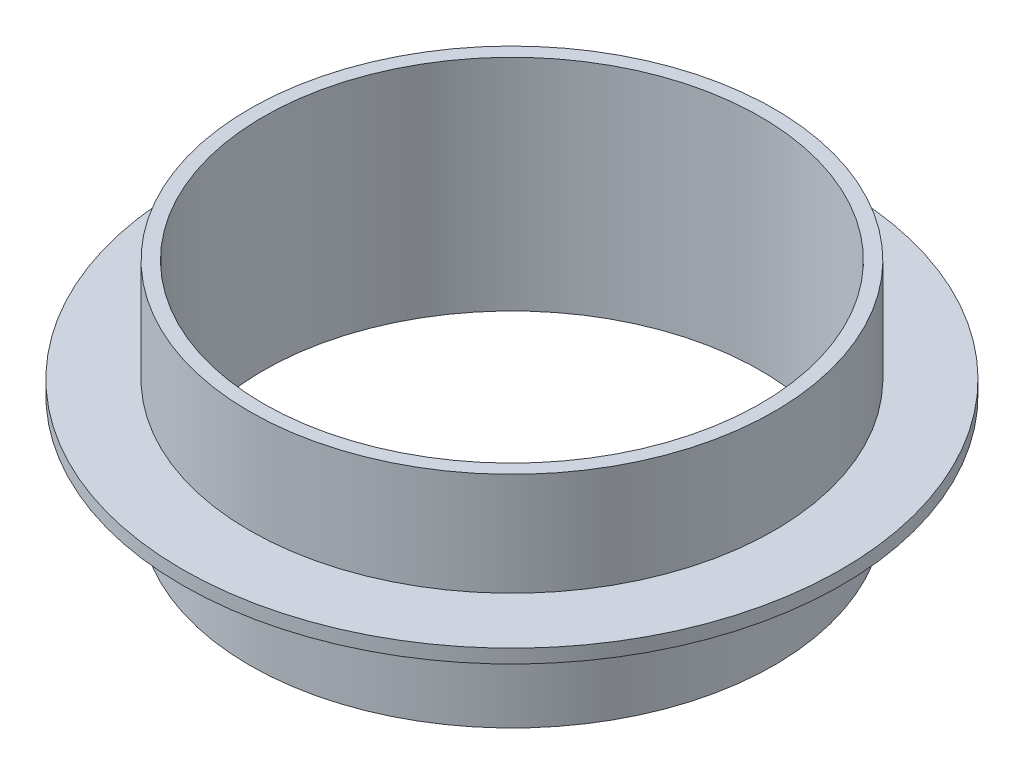
SolidWorks part; units mm, degrees
ref_plane "Front Plane" through (0, 0, 0) normal (0, 0, 1) x (1, 0, 0)
ref_plane "Top Plane" through (0, 0, 0) normal (0, 1, 0) x (1, 0, 0)
ref_plane "Right Plane" through (0, 0, 0) normal (1, 0, 0) x (0, 0, -1)
sketch "Sketch1" plane through (0, 0, 0) normal (0, 1, 0) x (1, 0, 0)
  circle A0 centre (0, 0) radius 57.4675
  circle A1 centre (0, 0) radius 60.6425
  dimension "D1" = 114.935
  dimension "D2" = 3.175
extrude "Boss-Extrude1" add sketch "Sketch1" along normal blind 50.8
sketch "Sketch2" plane through (0, 50.8, 0) normal (0, 1, 0) x (1, 0, 0)
  circle A0 centre (0, 0) radius 76.2
  circle A1 centre (0, 0) radius 60.6425 construction
  circle A2 centre (0, 0) radius 60.6425
  dimension "D1" = 152.4
extrude "Boss-Extrude2" add sketch "Sketch2" against normal blind 3.175 from offset 23.8125 offset against normal yes
hole_wizard "1/4 Clearance Hole1" positions "Sketch4" profile "Sketch3" hole size "1/4" standard "ANSI Inch"
sketch "Sketch4" plane through (0, 26.9875, 0) normal (0, 1, 0) x (1, 0, 0)
  line L0 (-76.2, 0) -> (-60.6425, 0) construction
  circle A0 centre (0, 0) radius 76.2 construction
  circle A1 centre (0, 0) radius 60.6425 construction
  point P0 (-68.4213, 0)
sketch "Sketch3" plane through (-68.4213, 26.9875, 0) normal (1, 0, 0) x (0, 0, 1)
  line L0 (0, 0) -> (0, 40.3151)
  line L1 (0, 40.3151) -> (3.2639, 38.354)
  line L2 (3.2639, 38.354) -> (3.2639, 0)
  line L5 (3.2639, 0) -> (0, 0)
  line L10 (0, 40.3151) -> (-3.2639, 38.354) construction
  line L11 (0, -6.35) -> (0, 107.95) construction
  dimension "Hole Dia." = 6.5278
  dimension "Hole Depth" = 38.354
  dimension "Drill Angle" = 118
